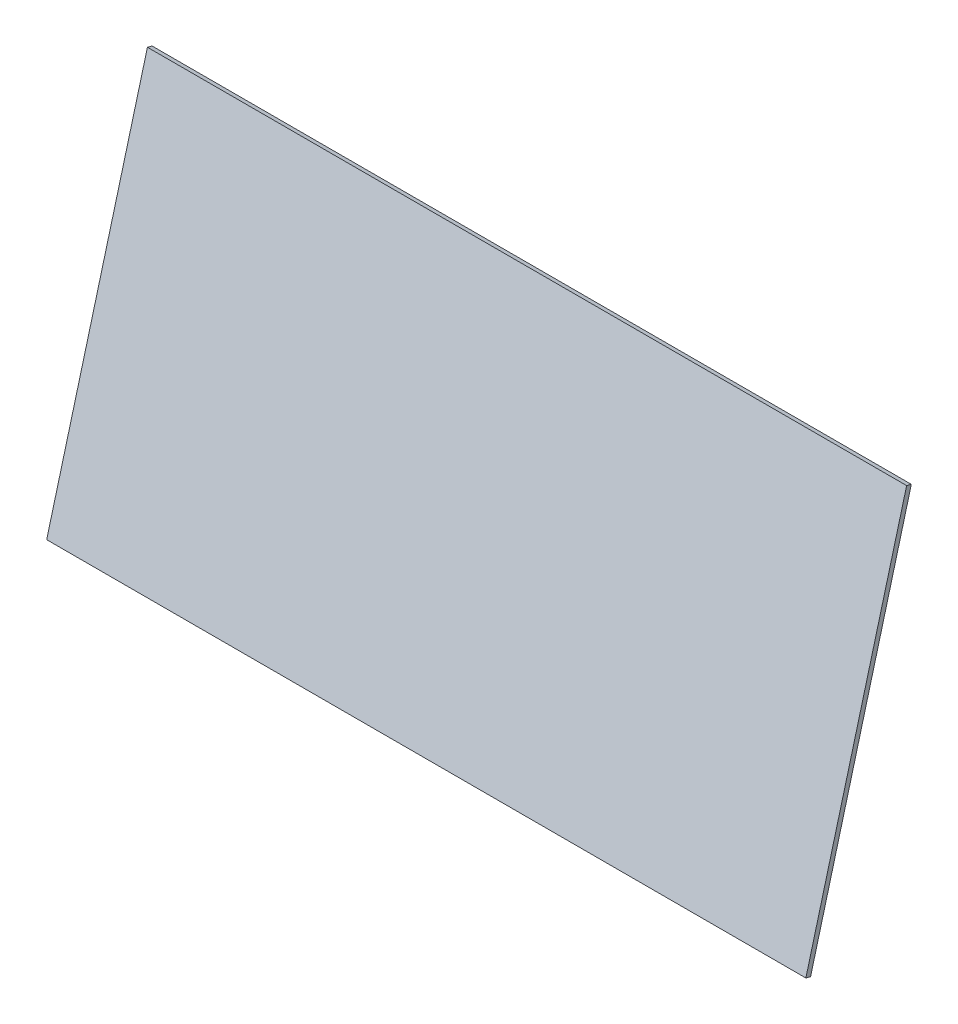
SolidWorks part; units mm, degrees
ref_plane "Front Plane" through (0, 0, 0) normal (0, 0, 1) x (1, 0, 0)
ref_plane "Top Plane" through (0, 0, 0) normal (0, 1, 0) x (1, 0, 0)
ref_plane "Right Plane" through (0, 0, 0) normal (1, 0, 0) x (0, 0, -1)
sketch "Sketch1" plane through (0, 0, 0) normal (1, 0, 0) x (0, 0, -1)
  line L0 (0, 0) -> (10.3528, 38.637)
extrude "Extrude-Thin1" add sketch "Sketch1" against normal blind 78 thin
